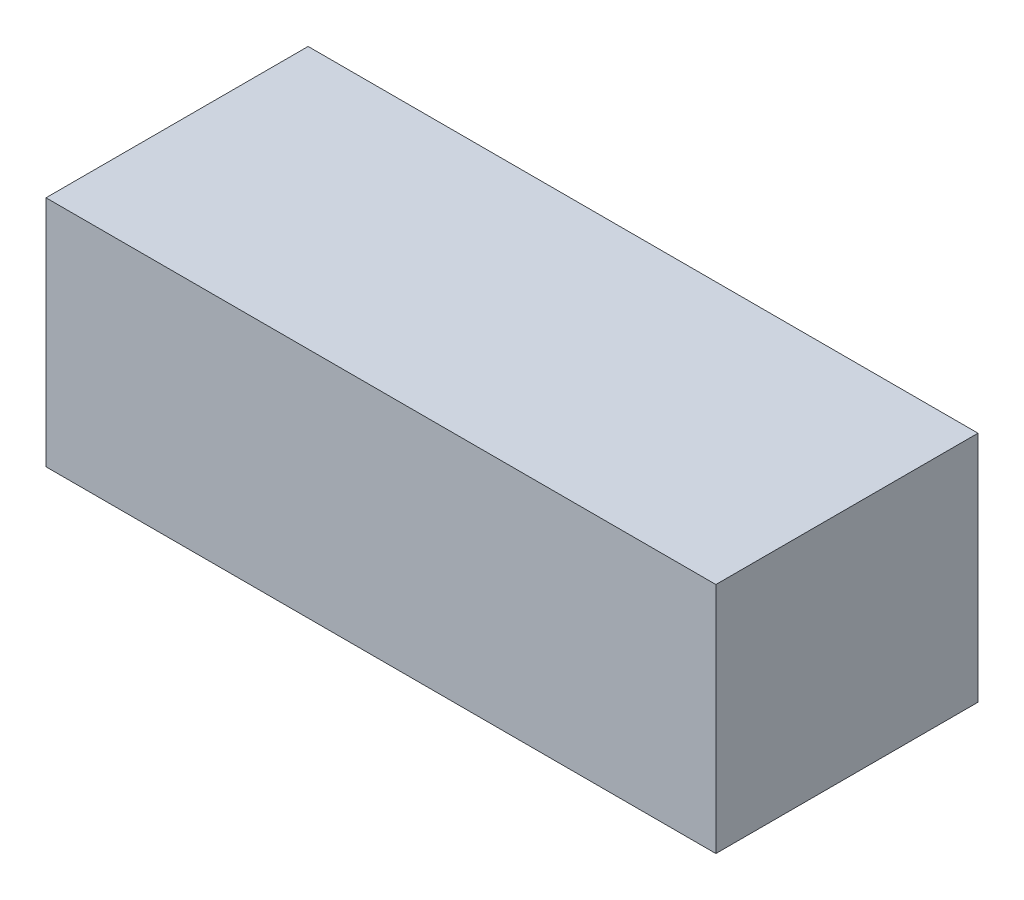
SolidWorks part; units mm, degrees
ref_plane "前视基准面" through (0, 0, 0) normal (0, 0, 1) x (1, 0, 0)
ref_plane "上视基准面" through (0, 0, 0) normal (0, 1, 0) x (1, 0, 0)
ref_plane "右视基准面" through (0, 0, 0) normal (1, 0, 0) x (0, 0, -1)
other "Configuration Table"
sketch "草图1" plane through (0, 0, 0) normal (0, 1, 0) x (1, 0, 0)
  line L0 (0, 9) -> (0, -9) construction
  line L1 (-23, 9) -> (23, 9)
  line L2 (-23, 9) -> (-23, -9)
  line L3 (-23, -9) -> (23, -9)
  line L4 (23, 9) -> (23, -9)
  line L6 (-23, 0) -> (23, 0) construction
  dimension "D1" = 46
  dimension "D2" = 18
extrude "凸台-拉伸1" add sketch "草图1" along normal blind 16
sketch "草图2" plane through (0, 16, 0) normal (0, 1, 0) x (1, 0, 0)
  text T0 "Li-ion" font "@Microsoft YaHei UI" height 3.5
sketch "草图3" plane through (0, 0, -9) normal (0, 0, -1) x (-1, 0, 0)
  text T0 "Li-ion" font "@Microsoft YaHei UI" height 3.5
sketch "草图4" plane through (0, 0, 0) normal (0, -1, 0) x (1, 0, 0)
  text T0 "Li-ion" font "@Microsoft YaHei UI" height 3.5
sketch "草图5" plane through (0, 0, 9) normal (0, 0, 1) x (1, 0, 0)
  text T0 "Li-ion" font "@Microsoft YaHei UI" height 3.5
